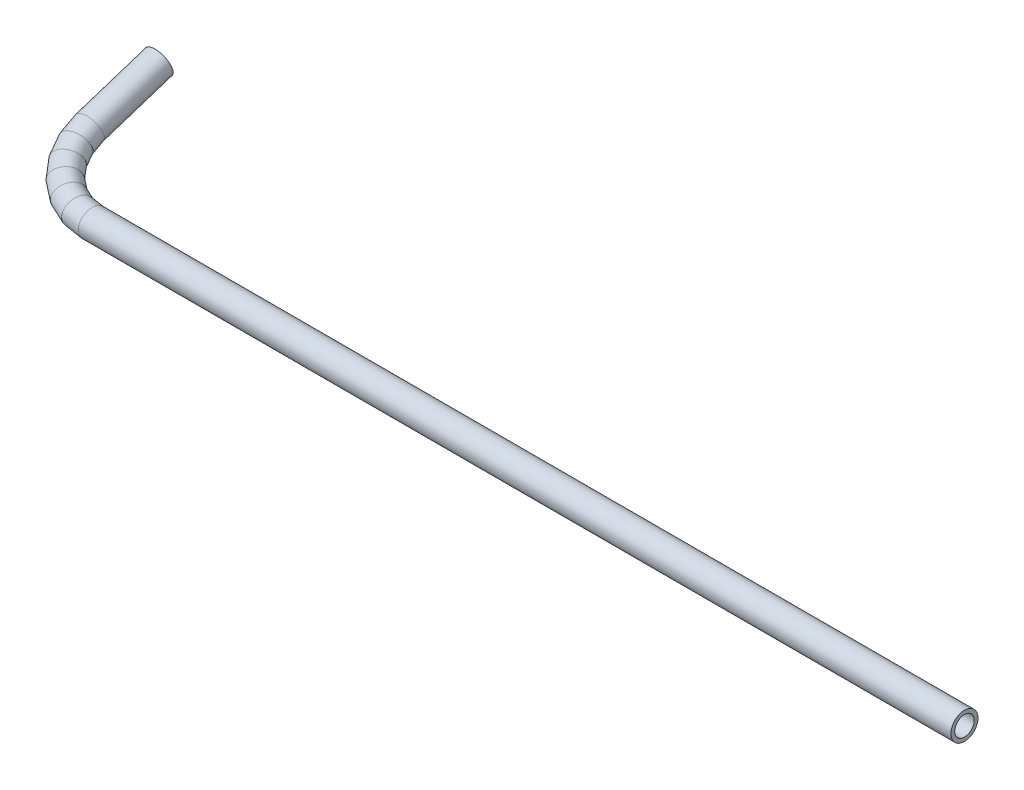
SolidWorks part; units mm, degrees
ref_plane "Front Plane" through (0, 0, 0) normal (0, 0, 1) x (1, 0, 0)
ref_plane "Top Plane" through (0, 0, 0) normal (0, 1, 0) x (1, 0, 0)
ref_plane "Right Plane" through (0, 0, 0) normal (1, 0, 0) x (0, 0, -1)
sketch3d "Path"
  line L0 (-1894.688, 10.1976, -31.3849) -> (-2099.188, 10.1976, -31.3849)
  line L1 (-2099.188, 10.1976, -31.3849) -> (-2103.0702, 10.3555, -31.871)
  line L2 (-2103.0702, 10.3555, -31.871) -> (-2106.688, 10.8186, -33.2961)
  line L3 (-2106.688, 10.8186, -33.2961) -> (-2109.7946, 11.5552, -35.5632)
  line L4 (-2109.7946, 11.5552, -35.5632) -> (-2112.1783, 12.5152, -38.5178)
  line L5 (-2112.1783, 12.5152, -38.5178) -> (-2113.6768, 13.6331, -41.9584)
  line L6 (-2113.6768, 13.6331, -41.9584) -> (-2114.188, 14.8328, -45.6507)
  line L7 (-2114.188, 14.8328, -45.6507) -> (-2114.188, 20.1325, -61.9613)
ref_plane "Start Plane" through (-1894.688, 0, 0) normal (1, 0, 0) x (0, 0, -1)
sketch "Profile" plane through (-1894.688, 0, 0) normal (1, 0, 0) x (0, 0, -1)
  circle A0 centre (31.3849, 10.1976) radius 3.175
  circle A1 centre (31.3849, 10.1976) radius 2.286
sweep "Tube" add profiles "Profile" path "Path"
